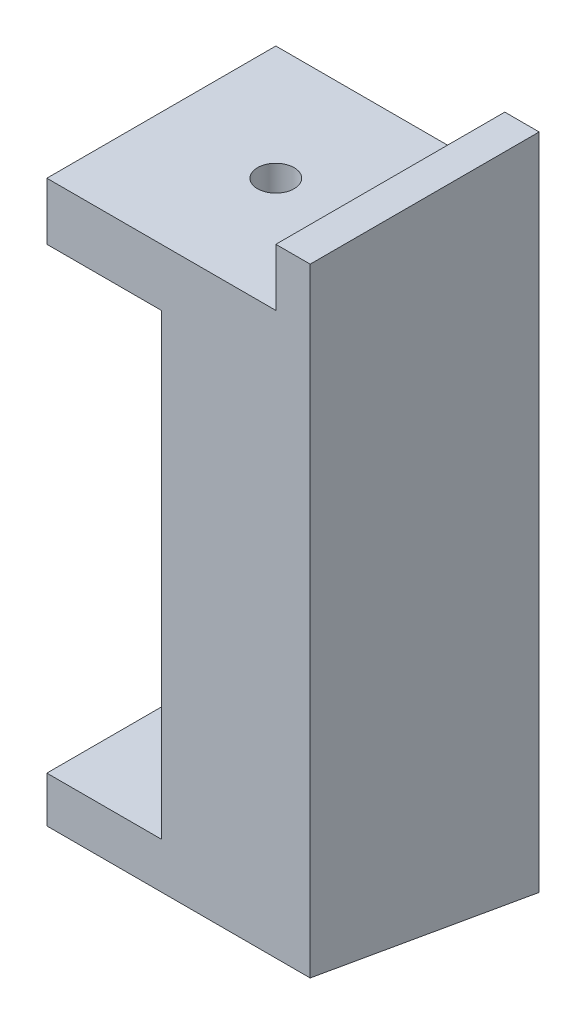
SolidWorks part; units mm, degrees
ref_plane "Front Plane" through (0, 0, 0) normal (0, 0, 1) x (1, 0, 0)
ref_plane "Top Plane" through (0, 0, 0) normal (0, 1, 0) x (1, 0, 0)
ref_plane "Right Plane" through (0, 0, 0) normal (1, 0, 0) x (0, 0, -1)
sketch "Sketch2" plane through (0, 0, 0) normal (0, 0, 1) x (1, 0, 0)
  line L1 (-10, 2.5) -> (10, 2.5)
  line L2 (-10, 2.5) -> (-10, -2.5)
  line L3 (-10, -2.5) -> (10, -2.5)
  line L5 (-10, 2.5) -> (10, -2.5) construction
  line L6 (-10, -2.5) -> (10, 2.5) construction
  line L7 (10, -2.5) -> (13, -2.5)
  line L8 (10, 2.5) -> (10, 7.5)
  line L9 (10, 7.5) -> (13, 7.5)
  line L10 (13, -2.5) -> (13, 7.5)
  point P0 (0, 0)
  dimension "D1" = 20
  dimension "D2" = 5
  dimension "D3" = 3
  dimension "D4" = 10
extrude "Boss-Extrude1" add sketch "Sketch2" along normal blind 20
sketch "Sketch3" plane through (0, 2.5, 0) normal (0, 1, 0) x (1, 0, 0)
  line L0 (10, 0) -> (-10, 0) construction
  circle A0 centre (0, -10) radius 1.6
  dimension "D1" = 10
  dimension "D2" = 3.2
extrude "Cut-Extrude1" cut sketch "Sketch3" against normal blind 20
sketch "Sketch4" plane through (0, -2.5, 0) normal (0, -1, 0) x (1, 0, 0)
  line L0 (-10, 20) -> (13, 20) construction
  line L1 (13, 0) -> (8, 0)
  line L2 (13, 0) -> (13, 20)
  line L3 (13, 20) -> (8, 20)
  line L4 (8, 3) -> (8, 17)
  line L6 (8, 0) -> (0, 0)
  line L8 (8, 3) -> (0, 3)
  line L9 (0, 0) -> (0, 3)
  line L10 (8, 20) -> (0, 20)
  line L12 (8, 17) -> (0, 17)
  line L13 (0, 20) -> (0, 17)
  dimension "D1" = 5
  dimension "D2" = 3
  dimension "D3" = 3
extrude "Boss-Extrude2" add sketch "Sketch4" along normal blind 40
fillet "Fillet1" radius 2 2 edges at (8, -22.5, 3) (8, -22.5, 17)
sketch "Sketch5" plane through (13, 0, 0) normal (1, 0, 0) x (0, 0, -1)
  line L0 (-20, -42.5) -> (-20, -46.5)
  line L1 (-20, -46.5) -> (0, -50.0265)
  line L2 (0, -50.0265) -> (0, -42.5)
  line L3 (-20, -42.5) -> (0, -42.5)
  dimension "D1" = 4
  dimension "D2" = 100
extrude "Boss-Extrude3" add sketch "Sketch5" against normal blind 23
sketch "Sketch6" plane through (0, -42.5, 0) normal (0, 1, 0) x (1, 0, 0)
  line L0 (-10, 0) -> (-10, -20) construction
  circle A0 centre (-1, -10) radius 3.2
  dimension "D1" = 6.4
  dimension "D2" = 9
extrude "Cut-Extrude2" cut sketch "Sketch6" against normal blind 13
